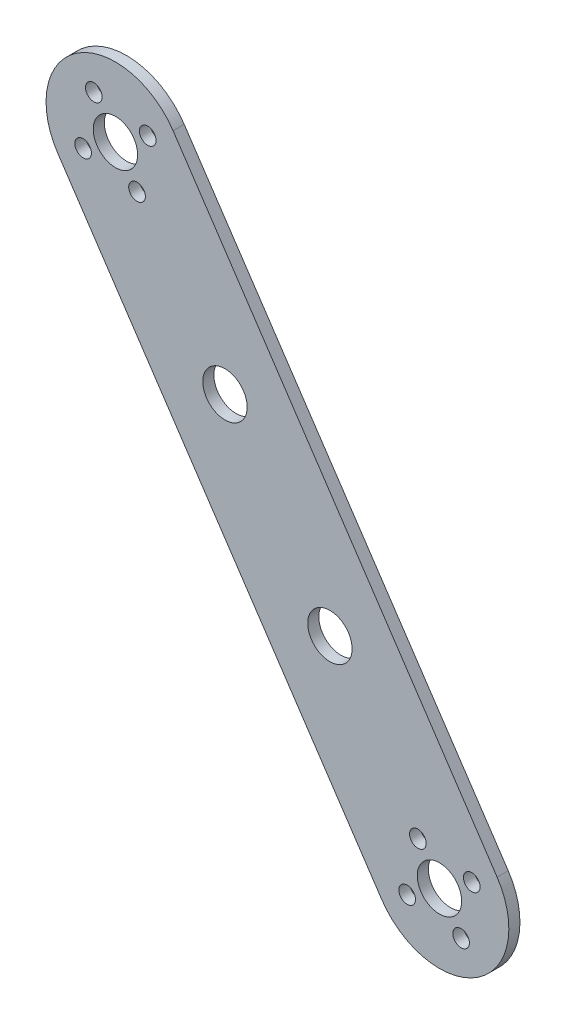
SolidWorks part; units mm, degrees
material "6061-T6 (SS)"
ref_plane "前视基准面" through (0, 0, 0) normal (0, 0, 1) x (1, 0, 0)
ref_plane "上视基准面" through (0, 0, 0) normal (0, 1, 0) x (1, 0, 0)
ref_plane "右视基准面" through (0, 0, 0) normal (1, 0, 0) x (0, 0, -1)
sketch "草图1" plane through (0, 0, 0) normal (0, 0, 1) x (1, 0, 0)
  line L12 (-61.4888, 124.7249) -> (-3.1101, 37.4498)
  line L13 (-23.8899, 23.5502) -> (-82.2685, 110.8252)
  circle A2 centre (-66.0603, 121.667) radius 1.5
  circle A4 centre (-75.7706, 123.5934) radius 1.5
  circle A6 centre (-67.9867, 111.9567) radius 1.5
  circle A10 centre (-71.8787, 117.775) radius 4
  circle A12 centre (-77.697, 113.8831) radius 1.5
  circle A14 centre (-52.1411, 88.2678) radius 1.5 construction
  arc A16 (-23.8899, 23.5502) -> (-3.1101, 37.4498) centre (-13.5, 30.5) ccw
  arc A17 (-61.4888, 124.7249) -> (-82.2685, 110.8252) centre (-71.8787, 117.775) ccw
  circle A20 centre (-19.3183, 26.6081) radius 1.5
  circle A22 centre (-9.6081, 24.6817) radius 1.5
  circle A24 centre (-17.3919, 36.3183) radius 1.5
  circle A28 centre (-13.5, 30.5) radius 4
  circle A30 centre (-7.6817, 34.3919) radius 1.5
  circle A31 centre (-52.1411, 88.2678) radius 4
  circle A32 centre (-33.2375, 60.0073) radius 1.5 construction
  circle A33 centre (-33.2375, 60.0073) radius 4
  dimension "D1" = 2.5
extrude "凸台-拉伸1" add sketch "草图1" along normal blind 2
